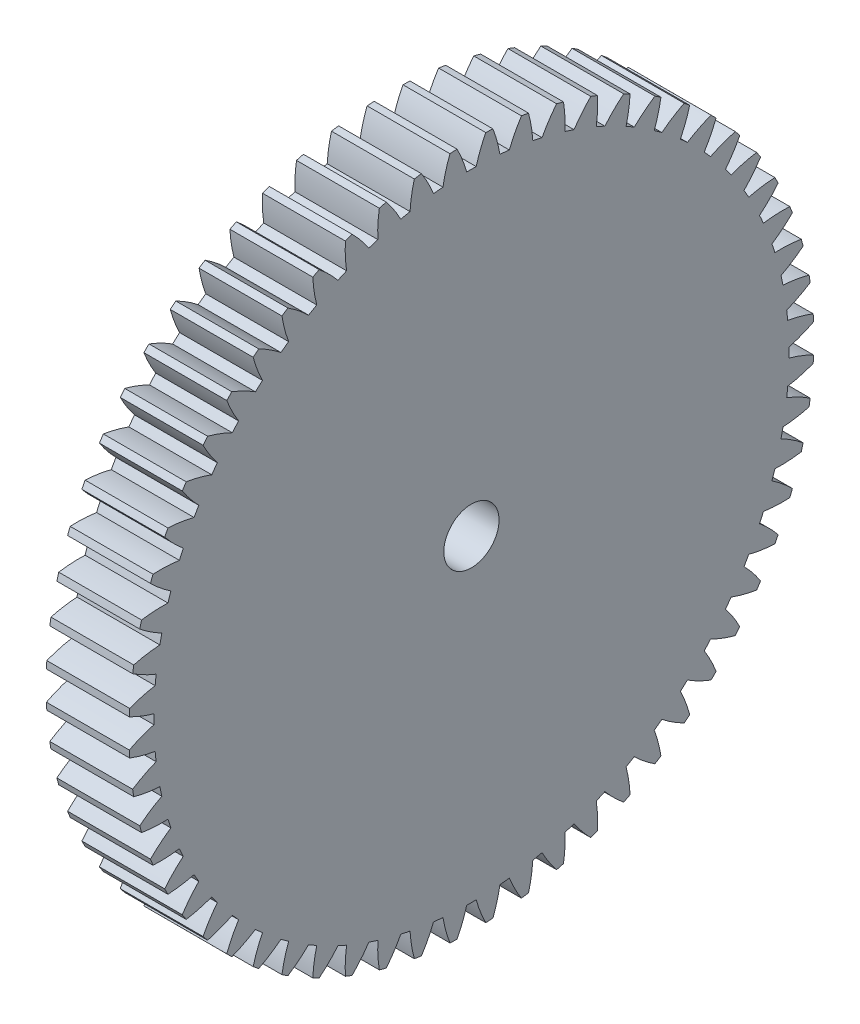
SolidWorks part; units mm, degrees
material "ABS"
ref_plane "Plane1" through (0, 0, 0) normal (0, 0, 1) x (1, 0, 0)
ref_plane "Plane2" through (0, 0, 0) normal (0, 1, 0) x (1, 0, 0)
ref_plane "Plane3" through (0, 0, 0) normal (1, 0, 0) x (0, 0, -1)
sketch "HoldingSke" plane through (0, 0, 0) normal (0, 1, 0) x (1, 0, 0)
  line L0 (0, 0) -> (1.25, -2.1651)
  line L1 (-15, 0) -> (100, 0) construction
  line L2 (0, 0) -> (-2.1039, 2.3779)
  line L3 (0, 0) -> (-11.863, 4.5341)
  line L4 (0, 0) -> (4.318, 7.479)
  line L5 (0, 0) -> (-46.8476, -17.4728)
  line L6 (0, 0) -> (-2.4869, -1.6779)
  line L7 (-2.1039, 2.3779) -> (8.6586, 51.2059)
  line L8 (-76.2, 54.61) -> (-75.9, 54.61)
  line L9 (-71.009, 38.7566) -> (-53.1078, 45.2721)
  line L10 (-76.2, 71.12) -> (104.1128, 71.12)
  line L11 (0, 0) -> (-3, 0)
  line L12 (-76.2, 101.6) -> (-76.185, 101.6)
  line L13 (24.9733, 27.94) -> (52.9518, 28.4284)
  line L14 (24.9733, 27.94) -> (24.9743, 27.94)
  line L15 (24.9733, 27.94) -> (100.4006, 29.5858)
  line L16 (-63.627, -0.4) -> (-12.827, -0.4)
  circle A0 centre (0, 0) radius 1
  circle A1 centre (0, 0) radius 11.499
  circle A2 centre (0, 0) radius 37.5
  circle A3 centre (0, 0) radius 1
  dimension "MHD" = 22.998
  dimension "Hub_dia" = 75
  dimension "Bore" = 2
  dimension "MBD" = 2
  dimension "Num_teeth" = 60
  dimension "Pitch" = 2.5
  dimension "Overall_len" = 50
  dimension "Show_teeth" = 60
  dimension "Thickness" = 3
  dimension "OAL" = 50.0001
  dimension "T_dim" = 0.3
  dimension "Ap" = 20
  dimension "H" = 19.05
  dimension "Pitch_radius" = 180.3128
  dimension "Width" = 3
  dimension "Backlash" = 0.015
  dimension "Addendum_fac" = 1
  dimension "Dedendum_fac" = 1.25
  dimension "Clearance_fac" = 0.25
  dimension "Dedendum_add" = 0.001
  dimension "Module" = 0.4
sketch "BasProSke" plane through (0, 0, 0) normal (0, 1, 0) x (1, 0, 0)
  line L0 (-10, 0) -> (60, 0) construction
  line L1 (0, 0) -> (0, 12.4)
  line L2 (0, 0) -> (3, 0)
  line L3 (3, 0) -> (3, 12.4)
  line L4 (3, 12.4) -> (0, 12.4)
  dimension "Thickness" = 3
  dimension "Diameter" = 24.8
revolve "Base-Revolve" add sketch "BasProSke" angle 360 about L0
sketch "TooCutSke" plane through (0, 0, 0) normal (1, 0, 0) x (0, 0, -1)
  line L1 (0, 0) -> (0, 107) construction
  line L2 (0, 0) -> (-0.3404, 11.9952) construction
  line L3 (0, 0) -> (-1.2557, 23.9602) construction
  line L4 (-0.3404, 11.9952) -> (-0.6279, 11.9801) construction
  arc A0 (0.1716, 11.4977) -> (-0.1716, 11.4977) centre (0, 0) ccw
  arc A1 (0.5324, 12.414) -> (-0.5324, 12.414) centre (0, 0) ccw
  circle A2 centre (0, 0) radius 12 construction
  circle A3 centre (0, 0) radius 11.2763 construction
  arc A4 (-0.1716, 11.4977) -> (-0.5324, 12.414) centre (-4.7946, 10.2062) ccw
  arc A5 (0.5324, 12.414) -> (0.1716, 11.4977) centre (4.7946, 10.2062) ccw
  dimension "Root_dia" = 22.998
  dimension "Overcut_dia" = 24.8508
  dimension "Pitch_dia" = 24
  dimension "Base_dia" = 22.5526
  dimension "Flank_rad" = 4.8
  dimension "Half_ang" = 3
  dimension "Half_CT" = 0.2879
extrude "ToothCut" cut sketch "TooCutSke" along normal through all
fillet "Breaks" [suppressed] radius 0.008
fillet "RootFillets" [suppressed] radius 0.101
pattern_circular "TeethCuts" count 60 every 6 about axis through (-10, 0, 0) along (1, 0, 0) of "ToothCut", "RootFillets", "Breaks"
sketch "HubNeaOneSke" plane through (0, 0, 0) normal (-1, 0, 0) x (0, 0, 1)
  circle A0 centre (0, 0) radius 11.499
  dimension "Diameter" = 22.998
extrude "HubNearOne" [suppressed] add sketch "HubNeaOneSke" along normal blind 47.0001
sketch "HubNeaBotSke" plane through (0, 0, 0) normal (-1, 0, 0) x (0, 0, 1)
  circle A0 centre (0, 0) radius 11.499
  dimension "Diameter" = 22.998
extrude "HubNearBoth" [suppressed] add sketch "HubNeaBotSke" along normal blind 23.5
ref_plane "FarPln" through (3, 0, 0) normal (1, 0, 0) x (0, 0, -1)
sketch "HubFarSke" plane through (3, 0, 0) normal (1, 0, 0) x (0, 0, -1)
  circle A0 centre (0, 0) radius 11.499
  dimension "Diameter" = 22.998
extrude "HubFar" [suppressed] add sketch "HubFarSke" along normal blind 23.5
sketch "BorSke" plane through (0, 0, 0) normal (1, 0, 0) x (0, 0, -1)
  circle A0 centre (0, 0) radius 1
  dimension "Diameter" = 2
extrude "Bore" cut sketch "BorSke" along normal mid plane 100.0001
sketch "KeySke" plane through (0, 0, 0) normal (1, 0, 0) x (0, 0, -1)
  line L0 (-0.4, 0) -> (-0.4, 1.3)
  line L1 (-0.4, 1.3) -> (0.4, 1.3)
  line L2 (0.4, 1.3) -> (0.4, 0)
  line L3 (0, 0) -> (0, 34) construction
  line L4 (-0.4, 0) -> (0.4, 0)
  dimension "Offset" = 1.3
  dimension "Width" = 0.8
extrude "Keyway" [suppressed] cut sketch "KeySke" along normal mid plane 100.0001
pattern_circular "Keyway2" [suppressed] count 2 every 90 about axis through (-10, 0, 0) along (1, 0, 0)
sketch "Sketch1" plane through (0, 0, 0) normal (-1, 0, 0) x (0, 0, 1)
  circle A0 centre (0, 0) radius 2.5
  dimension "D1" = 5
extrude "Cut-Extrude1" cut sketch "Sketch1" against normal blind 1.5
equation "' \"Module@HoldingSke\" = 6.35"
equation "' \"Num_teeth@HoldingSke\" = 12"
equation "' \"Ap@HoldingSke\" =  20"
equation "' \"Ap@HoldingSke\" = 20"
equation "' \"Width@HoldingSke\" = 0.5 * 25.4"
equation "' \"Hub_dia@HoldingSke\"= 1 * 25.4"
equation "' \"Hub_dia@HoldingSke\" = 1 * 25.4"
equation "' \"Overall_len@HoldingSke\" = 1.0 * 25.4"
equation "' \"Bore@HoldingSke\" = 0.75 * 25.4"
equation "' \"T_dim@HoldingSke\" = 0.1 * 25.4"
equation "' \"Width@KeySke\" = 0.25 * 25.4"
equation "' \"Show_teeth@HoldingSke\" = 13"
equation "' \"Backlash@HoldingSke\" = 0.009 * 25.4"
equation "' \"Addendum_fac@HoldingSke\" = 1.0"
equation "' \"Dedendum_fac@HoldingSke\" = 1.25"
equation "' \"Dedendum_add@HoldingSke\" = 0.00005 * 25.4"
equation "' \"Clearance_fac@HoldingSke\" = 0.25"
equation "\"Pitch@HoldingSke\" = 1 / \"Module@HoldingSke\""
equation "\"Overcut_dia@TooCutSke\" = (\"Num_teeth@HoldingSke\" + 2 * \"Addendum_fac@HoldingSke\") / \"Pitch@HoldingSke\" + 0.002 * 25.4"
equation "\"Pitch_dia@TooCutSke\" = \"Num_teeth@HoldingSke\" / \"Pitch@HoldingSke\""
equation "\"Base_dia@TooCutSke\" = \"Num_teeth@HoldingSke\" / \"Pitch@HoldingSke\" * cos((\"Ap@HoldingSke\"  * 3.14159265 / 180))"
equation "\"Root_dia@TooCutSke\" = (\"Num_teeth@HoldingSke\" + 2) / \"Pitch@HoldingSke\" - 2 * (\"Addendum_fac@HoldingSke\" + \"Dedendum_fac@HoldingSke\") / \"Pitch@HoldingSke\" - \"Dedendum_add@HoldingSke\" * 2"
equation "\"Half_ang@TooCutSke\" = 180 / \"Num_teeth@HoldingSke\""
equation "\"Half_CT@TooCutSke\" = \"Num_teeth@HoldingSke\" / \"Pitch@HoldingSke\" * sin((3.14159265 / 2 / \"Num_teeth@HoldingSke\")) / 2 - 7 * \"Backlash@HoldingSke\" / 4"
equation "\"Flank_rad@TooCutSke\" = \"Num_teeth@HoldingSke\" / \"Pitch@HoldingSke\" / 5"
equation "\"Radius@RootFillets\" = \"Clearance_fac@HoldingSke\" / \"Pitch@HoldingSke\" + \"Dedendum_add@HoldingSke\""
equation "\"Break_rad@Breaks\" = 0.02 / \"Pitch@HoldingSke\""
equation "\"Thickness@HoldingSke\" = \"Width@HoldingSke\""
equation "\"OAL@HoldingSke\" = \"Thickness@HoldingSke\""
equation "\"MHD@HoldingSke\" = (\"Num_teeth@HoldingSke\" + 2) / \"Pitch@HoldingSke\" - 2 * (\"Addendum_fac@HoldingSke\" + \"Dedendum_fac@HoldingSke\")  / \"Pitch@HoldingSke\" - \"Dedendum_add@HoldingSke\" * 2"
equation "\"MBD@HoldingSke\" = (\"Num_teeth@HoldingSke\" + 2) / \"Pitch@HoldingSke\" - 2 * (\"Addendum_fac@HoldingSke\" + \"Dedendum_fac@HoldingSke\")  / \"Pitch@HoldingSke\" - \"Dedendum_add@HoldingSke\" * 2 - 0.002 * 25.4"
equation "\"MHD@HoldingSke\" = ((sgn( \"MHD@HoldingSke\" - \"Hub_dia@HoldingSke\" )-1)*( \"MHD@HoldingSke\" - \"Hub_dia@HoldingSke\" ))/-2+ \"Hub_dia@HoldingSke\""
equation "\"MBD@HoldingSke\" = ((sgn( \"MBD@HoldingSke\" - \"Bore@HoldingSke\" )-1)*( \"MBD@HoldingSke\" - \"Bore@HoldingSke\" ))/-2+ \"Bore@HoldingSke\""
equation "\"OAL@HoldingSke\" = ((sgn( \"OAL@HoldingSke\" - \"Overall_len@HoldingSke\" )+1)*( \"OAL@HoldingSke\" - \"Overall_len@HoldingSke\" ))/2 + \"Overall_len@HoldingSke\" + 0.000002 * 25.4"
equation "\"Num_teeth@TeethCuts\" = int( \"Show_teeth@HoldingSke\" ) + 1"
equation "\"Num_teeth@TeethCuts\" = ((sgn( \"Num_teeth@TeethCuts\" - \"Num_teeth@HoldingSke\" )-1)*( \"Num_teeth@TeethCuts\" - \"Num_teeth@HoldingSke\" ))/-2+ \"Num_teeth@HoldingSke\""
equation "\"Num_teeth@TeethCuts\" = ((sgn( \"Num_teeth@TeethCuts\" - 2.0)+1)*( \"Num_teeth@TeethCuts\" - 2.0))/2 +2.0"
equation "\"Angle@TeethCuts\" = 360.0 / \"Num_teeth@HoldingSke\""
equation "\"Diameter@BasProSke\" = (\"Num_teeth@HoldingSke\" + 2 * \"Addendum_fac@HoldingSke\") / \"Pitch@HoldingSke\""
equation "\"Thickness@BasProSke\"  = \"Thickness@HoldingSke\""
equation "' \"Fillet_rad@BasProSke\" =  \"Thickness@HoldingSke\" * 0.05"
equation "' \"Fillet_rad@BasProSke\" = \"Thickness@HoldingSke\" * 0.05"
equation "\"MHD@HoldingSke\" = ((sgn( \"MHD@HoldingSke\" - \"Root_dia@TooCutSke\" )-1)*( \"MHD@HoldingSke\" - \"Root_dia@TooCutSke\" ))/-2+ \"Root_dia@TooCutSke\""
equation "\"Diameter@HubNeaOneSke\" = \"MHD@HoldingSke\""
equation "\"Length@HubNearOne\" = \"OAL@HoldingSke\" - \"Thickness@BasProSke\""
equation "\"Diameter@HubNeaBotSke\" = \"MHD@HoldingSke\""
equation "\"Length@HubNearBoth\" = ( \"OAL@HoldingSke\" - \"Thickness@BasProSke\" ) / 2.0"
equation "\"Thickness@FarPln\" = \"Thickness@BasProSke\""
equation "\"Diameter@HubFarSke\" = \"MHD@HoldingSke\""
equation "\"Length@HubFar\" = ( \"OAL@HoldingSke\" - \"Thickness@BasProSke\" ) / 2.0"
equation "\"Diameter@BorSke\" = \"MBD@HoldingSke\""
equation "\"D1@Bore\" = \"OAL@HoldingSke\" * 2.0"
equation "\"D1@Keyway\" = \"OAL@HoldingSke\" * 2.0"
equation "\"Offset@KeySke\" = \"T_dim@HoldingSke\" + \"MBD@HoldingSke\" / 2.0"
